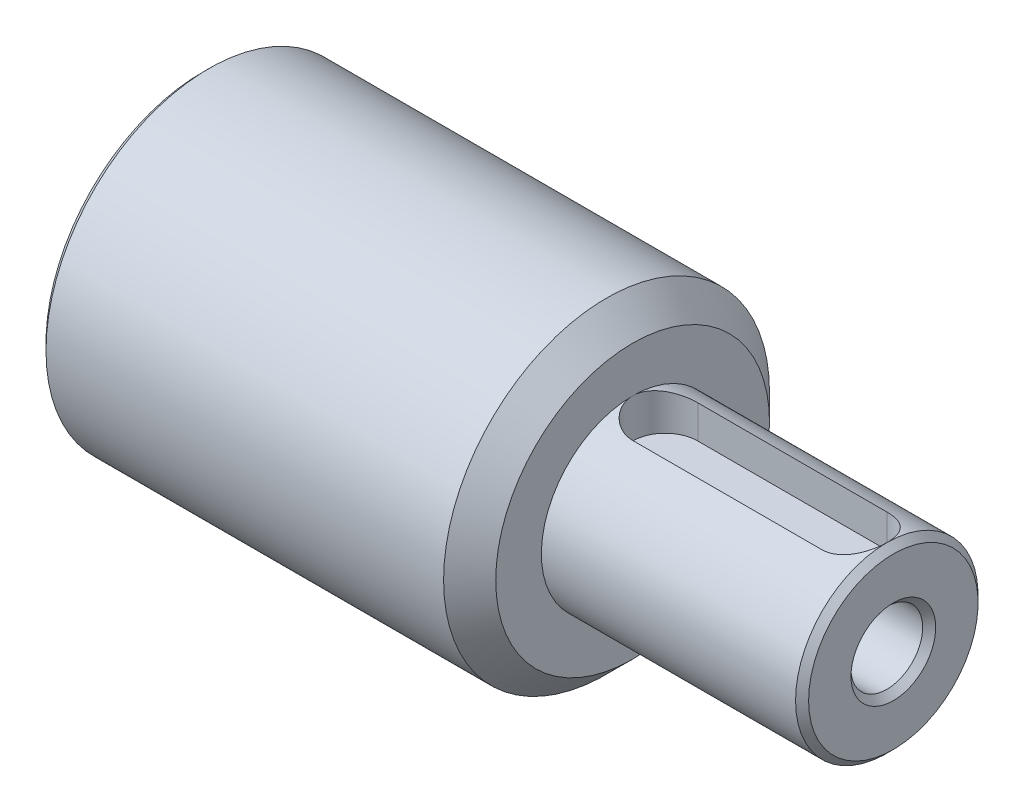
SolidWorks part; units mm, degrees
ref_plane "前视基准面" through (0, 0, 0) normal (0, 0, 1) x (1, 0, 0)
ref_plane "上视基准面" through (0, 0, 0) normal (0, 1, 0) x (1, 0, 0)
ref_plane "右视基准面" through (0, 0, 0) normal (1, 0, 0) x (0, 0, -1)
other "Configuration Table"
sketch "草图1" plane through (0, 0, 0) normal (0, 0, 1) x (1, 0, 0)
  line L0 (0, 0) -> (76.9333, 0) construction
  line L1 (0, 7) -> (0, 12.5)
  line L2 (0, 12.5) -> (33, 12.5)
  line L3 (33, 12.5) -> (33, 7)
  line L4 (33, 7) -> (53, 7)
  line L5 (53, 7) -> (53, 2.75)
  line L6 (53, 2.75) -> (28, 2.75)
  line L7 (28, 2.75) -> (28, 7)
  line L8 (28, 7) -> (0, 7)
  dimension "D1" = 25
  dimension "D2" = 28
  dimension "D3" = 5.5
  dimension "D4" = 14
  dimension "D5" = 33
  dimension "D6" = 20
  dimension "D7" = 14
revolve "旋转1" add sketch "草图1" angle 360 about L0
sketch "草图2" plane through (0, 0, 0) normal (-1, 0, 0) x (0, 0, 1)
  line L1 (-2.5, 9) -> (2.5, 9)
  line L2 (-2.5, 9) -> (-2.5, 0)
  line L3 (-2.5, 0) -> (2.5, 0)
  line L4 (2.5, 9) -> (2.5, 0)
  line L5 (-2.5, 9) -> (2.5, 0) construction
  line L6 (-2.5, 0) -> (2.5, 9) construction
  circle A2 centre (0, 0) radius 7 construction
  point P0 (0, 4.5)
  dimension "D1" = 16
  dimension "D2" = 5
extrude "切除-拉伸1" cut sketch "草图2" against normal blind 26
chamfer "倒角1" distance 2 angle 45 1 edges at (33, 0, 12.5)
chamfer "倒角2" distance 0.5 angle 45 4 edges at (53, 0, 7) (0, -7, 0) (53, 0, 2.75) (0, 0, 12.5)
fillet "圆角1" radius 1 1 edges at (28, 0, 7)
ref_plane "基准面1" through (0, 7, 0) normal (0, 1, 0) x (1, 0, 0)
sketch "草图3" plane through (0, 7, 0) normal (0, 1, 0) x (1, 0, 0)
  line L0 (35.5, 0) -> (50, 0) construction
  line L1 (35.5, 2.5) -> (50, 2.5)
  line L2 (35.5, -2.5) -> (50, -2.5)
  line L3 (52.5, -7) -> (52.5, 7) construction
  line L4 (52.5, 0) -> (33, 0) construction
  line L5 (33, -10.5) -> (33, 10.5) construction
  arc A0 (35.5, 2.5) -> (35.5, -2.5) centre (35.5, 0) ccw
  arc A1 (50, -2.5) -> (50, 2.5) centre (50, 0) ccw
  point P2 (42.75, 0)
  dimension "D1" = 14.5
extrude "切除-拉伸2" cut sketch "草图3" against normal blind 3
